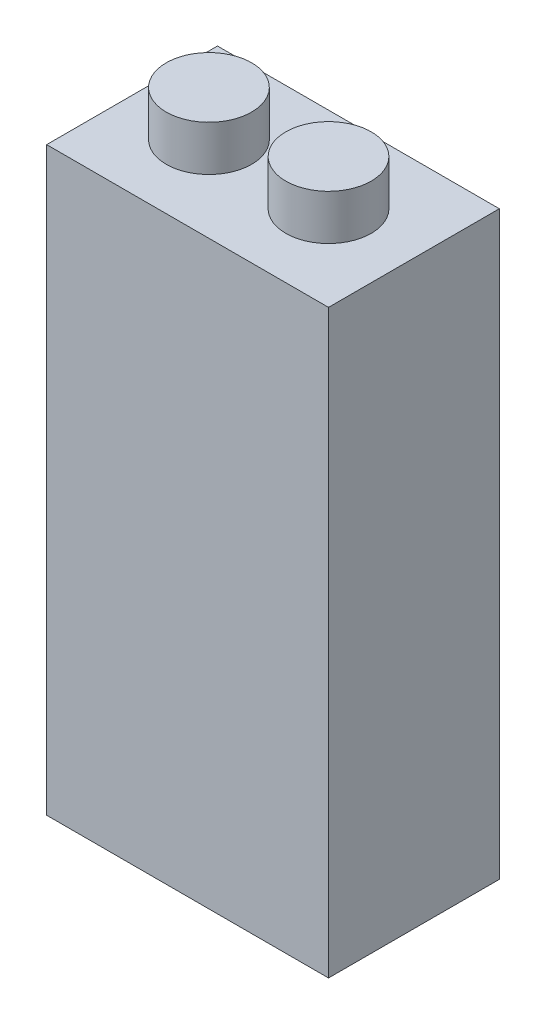
SolidWorks part; units mm, degrees
ref_plane "Front Plane" through (0, 0, 0) normal (0, 0, 1) x (1, 0, 0)
ref_plane "Top Plane" through (0, 0, 0) normal (0, 1, 0) x (1, 0, 0)
ref_plane "Right Plane" through (0, 0, 0) normal (1, 0, 0) x (0, 0, -1)
sketch "Sketch1" plane through (0, 0, 0) normal (0, 1, 0) x (1, 0, 0)
  line L1 (-16.5, 10) -> (16.5, 10)
  line L2 (-16.5, 10) -> (-16.5, -10)
  line L3 (-16.5, -10) -> (16.5, -10)
  line L4 (16.5, 10) -> (16.5, -10)
  dimension "D1" = 33
  dimension "D2" = 20
  dimension "D3" = 10
  dimension "D4" = 16.5
extrude "Boss-Extrude2" add sketch "Sketch1" along normal blind 68
sketch "Sketch2" plane through (0, 68, 0) normal (0, 1, 0) x (1, 0, 0)
  line L0 (-16.5, 10) -> (-16.5, -10) construction
  circle A0 centre (-7.5, 0) radius 5
  circle A1 centre (6.5, 0) radius 5
  dimension "D2" = 10
  dimension "D3" = 10
  dimension "D1" = 9
  dimension "D4" = 14
extrude "Boss-Extrude3" add sketch "Sketch2" along normal blind 5.3
